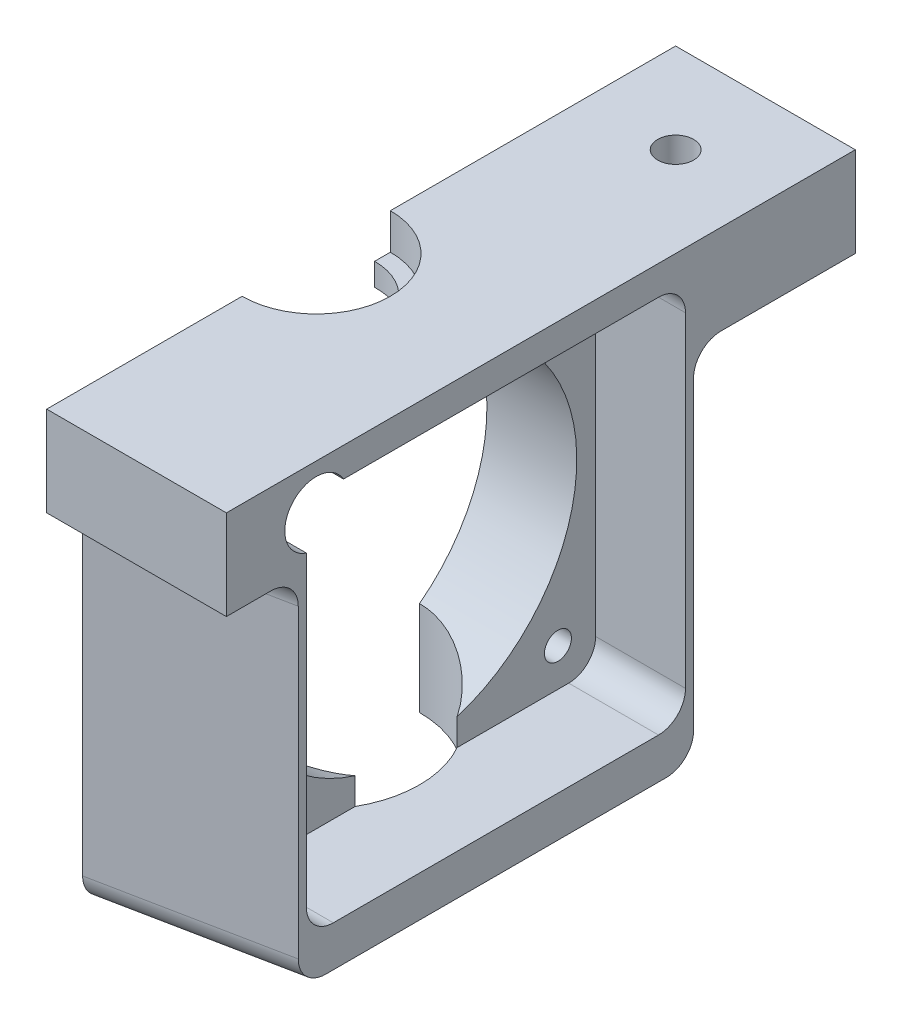
SolidWorks part; units mm, degrees
ref_plane "Front Plane" through (0, 0, 0) normal (0, 0, 1) x (1, 0, 0)
ref_plane "Top Plane" through (0, 0, 0) normal (0, 1, 0) x (1, 0, 0)
ref_plane "Right Plane" through (0, 0, 0) normal (1, 0, 0) x (0, 0, -1)
sketch "Sketch1" plane through (0, 0, 0) normal (0, 1, 0) x (1, 0, 0)
  line L1 (0, 0) -> (20, 0)
  line L2 (0, 0) -> (0, 70)
  line L3 (0, 70) -> (20, 70)
  line L4 (20, 0) -> (20, 70)
  dimension "D1" = 70
  dimension "D2" = 20
extrude "Boss-Extrude1" add sketch "Sketch1" along normal blind 20
sketch "Sketch4" plane through (0, 20, 0) normal (0, 1, 0) x (1, 0, 0)
  line L1 (0, 0) -> (20, 0)
  line L2 (0, 0) -> (0, 70)
  line L3 (0, 70) -> (20, 70)
  line L4 (20, 0) -> (20, 70)
extrude "Cut-Extrude3" cut sketch "Sketch4" against normal blind 10
sketch "Sketch5" plane through (0, 10, 0) normal (0, 1, 0) x (1, 0, 0)
  line L0 (0, 70) -> (0, 0) construction
  circle A0 centre (0, 30) radius 6.5
  dimension "D2" = 13
  dimension "D1" = 30
extrude "Cut-Extrude4" cut sketch "Sketch5" against normal blind 10
sketch "Sketch6" plane through (0, 10, 0) normal (0, 1, 0) x (1, 0, 0)
  circle A0 centre (0, 30) radius 8.25
  dimension "D1" = 16.5
extrude "Cut-Extrude5" cut sketch "Sketch6" against normal blind 4
sketch "Sketch7" plane through (20, 0, 0) normal (1, 0, 0) x (0, 0, -1)
  line L0 (0, 10) -> (0, 0) construction
  circle A0 centre (10, 5) radius 2
  point P4 (0, 5)
  dimension "D2" = 4
  dimension "D1" = 10
extrude "Cut-Extrude6" cut sketch "Sketch7" against normal blind 20
sketch "Sketch8" plane through (0, 10, 0) normal (0, 1, 0) x (1, 0, 0)
  line L0 (20, 70) -> (0, 70) construction
  circle A0 centre (10, 60) radius 2
  point P5 (10, 70)
  dimension "D1" = 4
  dimension "D2" = 10
  dimension "D3" = 0
extrude "Cut-Extrude7" cut sketch "Sketch8" against normal blind 20
sketch "Sketch9" plane through (0, 0, 0) normal (0, -1, 0) x (1, 0, 0)
  line L0 (20, 0) -> (20, -70) construction
  line L1 (10, -4) -> (20, -4)
  line L2 (10, -4) -> (10, -56)
  line L3 (10, -56) -> (20, -56)
  line L4 (20, -4) -> (20, -56)
  arc A0 (0, -36.5) -> (0, -23.5) centre (0, -30) ccw construction
  point P6 (10, -30)
  point P10 (6.5, -30)
  dimension "D1" = 3.5
  dimension "D2" = 52
  dimension "D3" = 0
extrude "Boss-Extrude2" add sketch "Sketch9" along normal blind 52
sketch "Sketch10" plane through (0, -52, 0) normal (0, -1, 0) x (1, 0, 0)
  line L1 (20, -4) -> (10, -4)
  line L2 (20, -4) -> (20, -56)
  line L3 (20, -56) -> (10, -56)
  line L4 (10, -4) -> (10, -56)
extrude "Cut-Extrude8" cut sketch "Sketch10" against normal blind 12
sketch "Sketch11" plane through (20, 0, 0) normal (1, 0, 0) x (0, 0, -1)
  line L0 (56, -40) -> (4, -40) construction
  line L1 (51.1, -35.4654) -> (8.9, -35.4654)
  line L2 (51.1, -35.4654) -> (51.1, 6.7346)
  line L3 (51.1, 6.7346) -> (8.9, 6.7346)
  line L4 (8.9, -35.4654) -> (8.9, 6.7346)
  point P4 (30, -35.4654)
  point P7 (30, -40)
  dimension "D1" = 42.2
  dimension "D2" = 42.2
  dimension "D3" = 0
extrude "Cut-Extrude9" cut sketch "Sketch11" against normal blind 5
sketch "Sketch12" plane through (15, 0, 0) normal (1, 0, 0) x (0, 0, -1)
  line L1 (8.9, -35.4654) -> (51.1, -35.4654)
  line L2 (8.9, -35.4654) -> (8.9, 6.7346)
  line L3 (8.9, 6.7346) -> (51.1, 6.7346)
  line L4 (51.1, -35.4654) -> (51.1, 6.7346)
extrude "Cut-Extrude10" cut sketch "Sketch12" against normal blind 5
sketch "Sketch13" plane through (10, 0, 0) normal (-1, 0, 0) x (0, 0, 1)
  line L1 (-56, 0) -> (-4, 0)
  line L2 (-56, 0) -> (-56, -40)
  line L3 (-56, -40) -> (-4, -40)
  line L4 (-4, 0) -> (-4, -40)
extrude "Boss-Extrude3" add sketch "Sketch13" along normal blind 10
sketch "Sketch14" plane through (0, 0, 0) normal (0, 1, 0) x (1, 0, 0)
  line L0 (0, 23.5) -> (0, 36.5) construction
  circle A0 centre (0, 30) radius 11.5
  dimension "D1" = 23
extrude "Cut-Extrude11" cut sketch "Sketch14" against normal blind 100
sketch "Sketch16" plane through (10, 0, 0) normal (1, 0, 0) x (0, 0, -1)
  circle A0 centre (30, -14.3654) radius 19
  dimension "D1" = 38
extrude "Cut-Extrude12" cut sketch "Sketch16" against normal blind 100
sketch "Sketch17" plane through (10, 0, 0) normal (1, 0, 0) x (0, 0, -1)
  line L1 (8.9, 3.3297) -> (8.9, -35.4654) construction
  line L2 (51.1, 6.7346) -> (10.9955, 6.7346) construction
  line L3 (51.1, -35.4654) -> (51.1, 6.7346) construction
  line L4 (8.9, -35.4654) -> (51.1, -35.4654) construction
  circle A0 centre (13.1, 2.5346) radius 1.5
  circle A1 centre (46.9, 2.5346) radius 1.5
  circle A2 centre (13.1, -31.2654) radius 1.5
  circle A3 centre (46.9, -31.2654) radius 1.5
  dimension "D1" = 3
  dimension "D5" = 3
  dimension "D7" = 3
  dimension "D8" = 3
  dimension "D2" = 4.2
  dimension "D3" = 4.2
  dimension "D4" = 4.2
  dimension "D6" = 4.2
extrude "Cut-Extrude13" cut sketch "Sketch17" against normal blind 100
sketch "Sketch19" plane through (0, -40, 0) normal (0, -1, 0) x (1, 0, 0)
  line L0 (20, -56) -> (20, -52)
  line L1 (20, -56) -> (20, -4) construction
  line L2 (20, -52) -> (0, -56)
  line L3 (0, -56) -> (20, -56)
  line L4 (20, -4) -> (20, -8)
  line L5 (20, -8) -> (0, -4)
  line L6 (0, -4) -> (20, -4)
  dimension "D1" = 4
  dimension "D2" = 4
extrude "Cut-Extrude14" cut sketch "Sketch19" against normal blind 40
fillet "Fillet1" radius 3 1 edges at (10, -40, -6)
fillet "Fillet2" radius 3 1 edges at (10, -40, -54)
fillet "Fillet3" radius 3 1 edges at (10, 0, -54)
fillet "Fillet4" radius 3 1 edges at (10, 0, -6)
fillet "Fillet5" radius 3 1 edges at (15, 6.7346, -51.1)
fillet "Fillet6" radius 3 1 edges at (15, -35.4654, -8.9)
fillet "Fillet7" radius 3 1 edges at (15, -35.4654, -51.1)
sketch "Sketch20" plane through (0, 0, 0) normal (-1, 0, 0) x (0, 0, 1)
  line L1 (-16.1, -31.2654) -> (-14.6, -33.8634)
  line L2 (-14.6, -33.8634) -> (-11.6, -33.8634)
  line L3 (-11.6, -33.8634) -> (-10.1, -31.2654)
  line L4 (-10.1, -31.2654) -> (-11.6, -28.6673)
  line L5 (-11.6, -28.6673) -> (-14.6, -28.6673)
  line L6 (-14.6, -28.6673) -> (-16.1, -31.2654)
  line L7 (-49.9, -31.2654) -> (-48.4, -33.8634)
  line L8 (-48.4, -33.8634) -> (-45.4, -33.8634)
  line L9 (-45.4, -33.8634) -> (-43.9, -31.2654)
  line L10 (-43.9, -31.2654) -> (-45.4, -28.6673)
  line L11 (-45.4, -28.6673) -> (-48.4, -28.6673)
  line L12 (-48.4, -28.6673) -> (-49.9, -31.2654)
  line L13 (-49.9, 2.5346) -> (-48.4, -0.0634)
  line L14 (-48.4, -0.0634) -> (-45.4, -0.0634)
  line L15 (-45.4, -0.0634) -> (-43.9, 2.5346)
  line L16 (-43.9, 2.5346) -> (-45.4, 5.1327)
  line L17 (-45.4, 5.1327) -> (-48.4, 5.1327)
  line L18 (-48.4, 5.1327) -> (-49.9, 2.5346)
  circle A0 centre (-13.1, -31.2654) radius 2.5981 construction
  circle A1 centre (-46.9, -31.2654) radius 2.5981 construction
  circle A2 centre (-46.9, 2.5346) radius 2.5981 construction
  dimension "D1" = 3
  dimension "D2" = 3
  dimension "D3" = 3
extrude "Cut-Extrude15" cut sketch "Sketch20" against normal blind 2.5
sketch "Sketch21" plane through (20, 0, 0) normal (1, 0, 0) x (0, 0, -1)
  circle A0 centre (10, 5) radius 3.5
  dimension "D1" = 7
extrude "Cut-Extrude16" cut sketch "Sketch21" against normal blind 13
